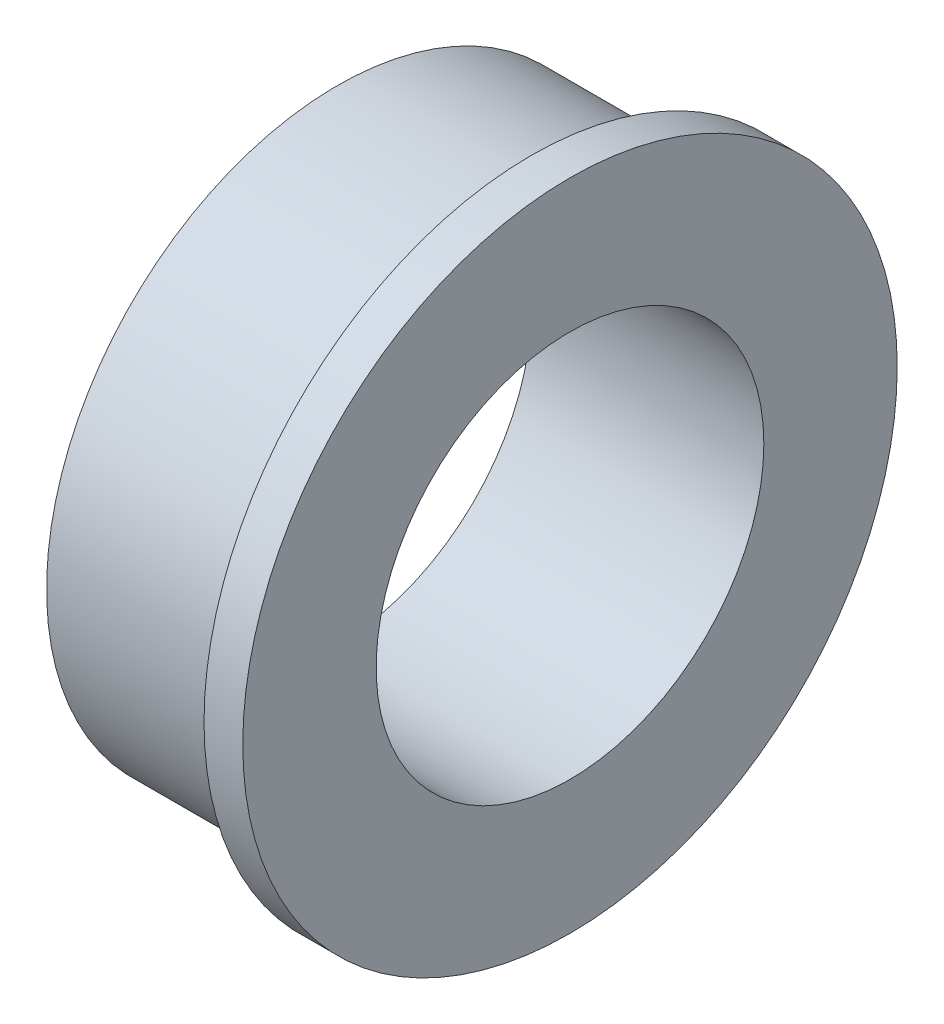
SolidWorks part; units mm, degrees
ref_plane "Front Plane" through (0, 0, 0) normal (0, 0, 1) x (1, 0, 0)
ref_plane "Top Plane" through (0, 0, 0) normal (0, 1, 0) x (1, 0, 0)
ref_plane "Right Plane" through (0, 0, 0) normal (1, 0, 0) x (0, 0, -1)
sketch "Sketch1" plane through (0, 0, 0) normal (1, 0, 0) x (0, 0, -1)
  circle A0 centre (0, 0) radius 3.175
  circle A1 centre (0, 0) radius 4.7625
  dimension "D1" = 6.35
  dimension "D2" = 9.525
extrude "Boss-Extrude1" add sketch "Sketch1" along normal blind 3.175
sketch "Sketch2" plane through (3.175, 0, 0) normal (1, 0, 0) x (0, 0, -1)
  circle A0 centre (0, 0) radius 3.175
  circle A1 centre (0, 0) radius 5.3594
  dimension "D1" = 10.7188
  dimension "D2" = 6.35
extrude "Boss-Extrude2" add sketch "Sketch2" along normal blind 0.635
